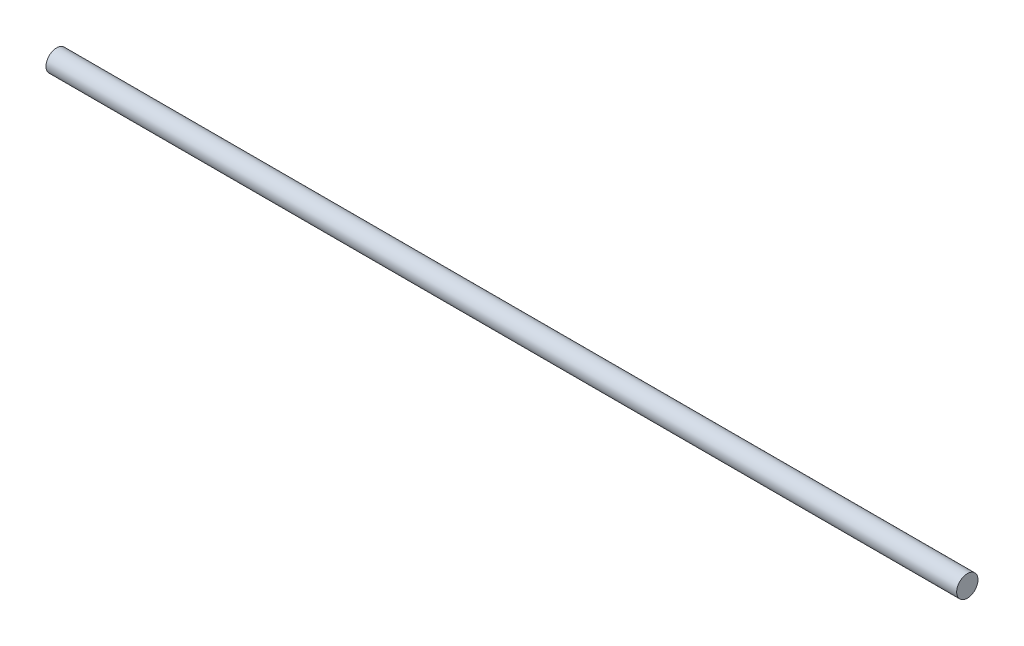
SolidWorks part; units mm, degrees
ref_plane "Front Plane" through (0, 0, 0) normal (0, 0, 1) x (1, 0, 0)
ref_plane "Top Plane" through (0, 0, 0) normal (0, 1, 0) x (1, 0, 0)
ref_plane "Right Plane" through (0, 0, 0) normal (1, 0, 0) x (0, 0, -1)
sketch "Sketch1" plane through (0, 0, 0) normal (1, 0, 0) x (0, 0, -1)
  circle A0 centre (0, 0) radius 4.7625
  dimension "D1" = 9.525
extrude "Boss-Extrude1" add sketch "Sketch1" along normal blind 406.4
